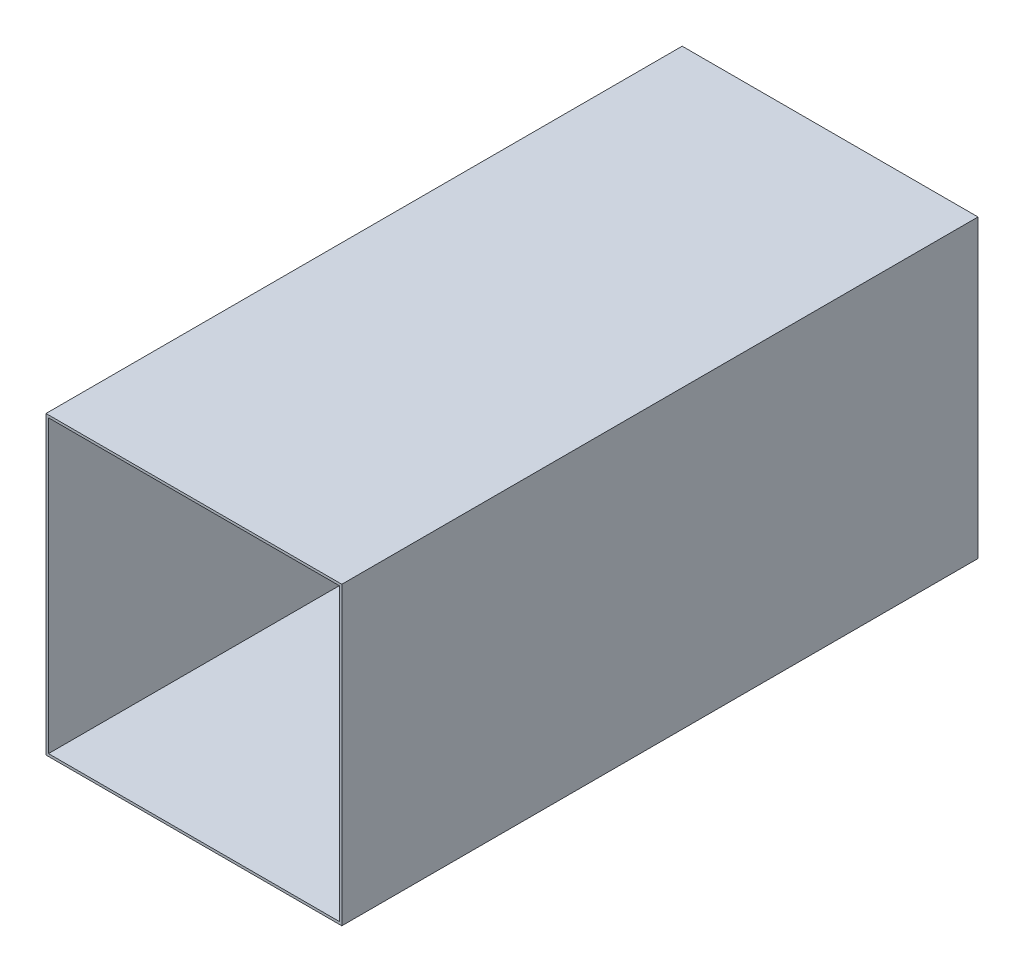
SolidWorks part; units mm, degrees
material "Beech"
ref_plane "Front Plane" through (0, 0, 0) normal (0, 0, 1) x (1, 0, 0)
ref_plane "Top Plane" through (0, 0, 0) normal (0, 1, 0) x (1, 0, 0)
ref_plane "Right Plane" through (0, 0, 0) normal (1, 0, 0) x (0, 0, -1)
sketch "Sketch1" plane through (0, 0, 0) normal (0, 0, 1) x (1, 0, 0)
  line L0 (-320, -320) -> (320, -320)
  line L1 (-320, -320) -> (-320, 320)
  line L2 (-320, 320) -> (320, 320)
  line L3 (320, -320) -> (320, 320)
  line L4 (-320, -320) -> (320, 320) construction
  line L5 (-320, 320) -> (320, -320) construction
  line L6 (-325.5, -325.5) -> (325.5, -325.5)
  line L7 (-325.5, -325.5) -> (-325.5, 325.5)
  line L8 (-325.5, 325.5) -> (325.5, 325.5)
  line L9 (325.5, -325.5) -> (325.5, 325.5)
  line L10 (-325.5, -325.5) -> (325.5, 325.5) construction
  line L11 (-325.5, 325.5) -> (325.5, -325.5) construction
  point P0 (0, 0)
  point P5 (0, 0)
  point P6 (0, 0)
  dimension "D1" = 640
extrude "Boss-Extrude1" add sketch "Sketch1" along normal blind 1400
